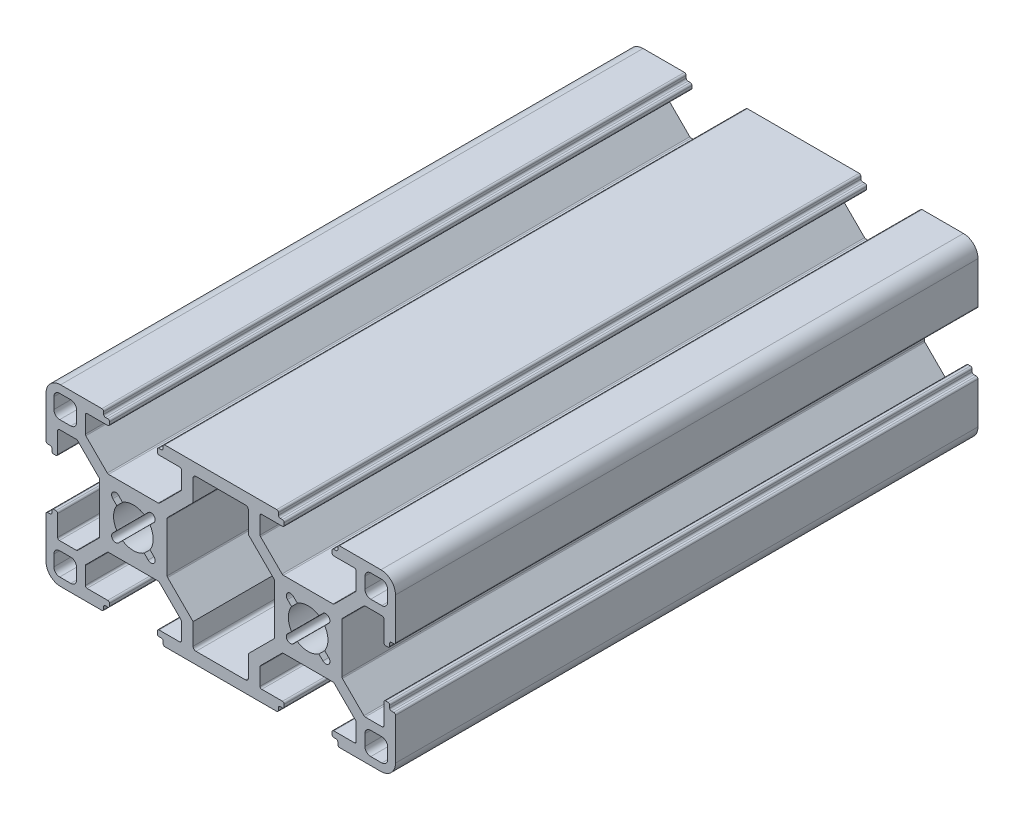
SolidWorks part; units mm, degrees
ref_plane "前视基准面" through (0, 0, 0) normal (0, 0, 1) x (1, 0, 0)
ref_plane "上视基准面" through (0, 0, 0) normal (0, 1, 0) x (1, 0, 0)
ref_plane "右视基准面" through (0, 0, 0) normal (1, 0, 0) x (0, 0, -1)
sketch "草图1" plane through (0, 0, 0) normal (0, 0, 1) x (1, 0, 0)
  line B0 (39.75, -10.75) -> (39.75, -12.65)
  line B1 (40.75, -13.65) -> (42.65, -13.65)
  line B2 (43.65, -12.65) -> (43.65, -10.75)
  line B3 (42.65, -9.75) -> (40.75, -9.75)
  line B4 (7.95, -13) -> (4.4, -13)
  line B5 (4.1, -13.3) -> (4.1, -13.7)
  line B6 (4.4, -14) -> (4.8, -14)
  line B7 (5.1, -14.3) -> (5.1, -14.7)
  line B8 (5.4, -15) -> (24.6, -15)
  line B9 (24.9, -14.7) -> (24.9, -14.3)
  line B10 (25.2, -14) -> (25.6, -14)
  line B11 (25.9, -13.7) -> (25.9, -13.3)
  line B12 (25.6, -13) -> (22.05, -13)
  line B13 (21.75, -12.7) -> (21.75, -9.7885)
  line B14 (21.8379, -9.5763) -> (25.5263, -5.8879)
  line B15 (25.7385, -5.8) -> (34.2615, -5.8)
  line B16 (34.4737, -5.8879) -> (38.1621, -9.5763)
  line B17 (38.25, -9.7885) -> (38.25, -12.7)
  line B18 (37.95, -13) -> (34.4, -13)
  line B19 (34.1, -13.3) -> (34.1, -13.7)
  line B20 (34.4, -14) -> (34.8, -14)
  line B21 (35.1, -14.3) -> (35.1, -14.7)
  line B22 (35.4, -15) -> (42.5, -15)
  line B23 (45, -12.5) -> (45, -5.4)
  line B24 (44.7, -5.1) -> (44.3, -5.1)
  line B25 (44, -4.8) -> (44, -4.4)
  line B26 (43.7, -4.1) -> (43.3, -4.1)
  line B27 (43, -4.4) -> (43, -7.95)
  line B28 (42.7, -8.25) -> (39.7885, -8.25)
  line B29 (39.5763, -8.1621) -> (35.8879, -4.4737)
  line B30 (35.8, -4.2615) -> (35.8, 4.2615)
  line B31 (35.8879, 4.4737) -> (39.5763, 8.1621)
  line B32 (39.7885, 8.25) -> (42.7, 8.25)
  line B33 (43, 7.95) -> (43, 4.4)
  line B34 (43.3, 4.1) -> (43.7, 4.1)
  line B35 (44, 4.4) -> (44, 4.8)
  line B36 (44.3, 5.1) -> (44.7, 5.1)
  line B37 (45, 5.4) -> (45, 12.5)
  line B38 (42.5, 15) -> (35.4, 15)
  line B39 (35.1, 14.7) -> (35.1, 14.3)
  line B40 (34.8, 14) -> (34.4, 14)
  line B41 (34.1, 13.7) -> (34.1, 13.3)
  line B42 (34.4, 13) -> (37.95, 13)
  line B43 (38.25, 12.7) -> (38.25, 9.7885)
  line B44 (38.1621, 9.5763) -> (34.4737, 5.8879)
  line B45 (34.2615, 5.8) -> (25.7385, 5.8)
  line B46 (25.5263, 5.8879) -> (21.8379, 9.5763)
  line B47 (21.75, 9.7885) -> (21.75, 12.7)
  line B48 (22.05, 13) -> (25.6, 13)
  line B49 (25.9, 13.3) -> (25.9, 13.7)
  line B50 (25.6, 14) -> (25.2, 14)
  line B51 (24.9, 14.3) -> (24.9, 14.7)
  line B52 (24.6, 15) -> (5.4, 15)
  line B53 (5.1, 14.7) -> (5.1, 14.3)
  line B54 (4.8, 14) -> (4.4, 14)
  line B55 (4.1, 13.7) -> (4.1, 13.3)
  line B56 (4.4, 13) -> (7.95, 13)
  line B57 (8.25, 12.7) -> (8.25, 9.7885)
  line B58 (8.1621, 9.5763) -> (4.4737, 5.8879)
  line B59 (4.2615, 5.8) -> (-4.2615, 5.8)
  line B60 (-4.4737, 5.8879) -> (-8.1621, 9.5763)
  line B61 (-8.25, 9.7885) -> (-8.25, 12.7)
  line B62 (-7.95, 13) -> (-4.4, 13)
  line B63 (-4.1, 13.3) -> (-4.1, 13.7)
  line B64 (-4.4, 14) -> (-4.8, 14)
  line B65 (-5.1, 14.3) -> (-5.1, 14.7)
  line B66 (-5.4, 15) -> (-12.5, 15)
  line B67 (-15, 12.5) -> (-15, 5.4)
  line B68 (-14.7, 5.1) -> (-14.3, 5.1)
  line B69 (-14, 4.8) -> (-14, 4.4)
  line B70 (-13.7, 4.1) -> (-13.3, 4.1)
  line B71 (-13, 4.4) -> (-13, 7.95)
  line B72 (-12.7, 8.25) -> (-9.7885, 8.25)
  line B73 (-9.5763, 8.1621) -> (-5.8879, 4.4737)
  line B74 (-5.8, 4.2615) -> (-5.8, -4.2615)
  line B75 (-5.8879, -4.4737) -> (-9.5763, -8.1621)
  line B76 (-9.7885, -8.25) -> (-12.7, -8.25)
  line B77 (-13, -7.95) -> (-13, -4.4)
  line B78 (-13.3, -4.1) -> (-13.7, -4.1)
  line B79 (-14, -4.4) -> (-14, -4.8)
  line B80 (-14.3, -5.1) -> (-14.7, -5.1)
  line B81 (-15, -5.4) -> (-15, -12.5)
  line B82 (-12.5, -15) -> (-5.4, -15)
  line B83 (-5.1, -14.7) -> (-5.1, -14.3)
  line B84 (-4.8, -14) -> (-4.4, -14)
  line B85 (-4.1, -13.7) -> (-4.1, -13.3)
  line B86 (-4.4, -13) -> (-7.95, -13)
  line B87 (-8.25, -12.7) -> (-8.25, -9.7885)
  line B88 (-8.1621, -9.5763) -> (-4.4737, -5.8879)
  line B89 (-4.2615, -5.8) -> (4.2615, -5.8)
  line B90 (4.4737, -5.8879) -> (8.1621, -9.5763)
  line B91 (8.25, -9.7885) -> (8.25, -12.7)
  line B92 (40.75, 9.75) -> (42.65, 9.75)
  line B93 (43.65, 10.75) -> (43.65, 12.65)
  line B94 (42.65, 13.65) -> (40.75, 13.65)
  line B95 (39.75, 12.65) -> (39.75, 10.75)
  line B96 (32.5456, 3.5355) -> (31.8577, 2.8476)
  line B97 (28.1423, 2.8476) -> (27.4544, 3.5355)
  line B98 (26.4645, 2.5456) -> (27.1524, 1.8577)
  line B99 (27.1524, -1.8577) -> (26.4645, -2.5456)
  line B100 (27.4544, -3.5355) -> (28.1423, -2.8476)
  line B101 (31.8577, -2.8476) -> (32.5456, -3.5355)
  line B102 (33.5355, -2.5456) -> (32.8476, -1.8577)
  line B103 (32.8476, 1.8577) -> (33.5355, 2.5456)
  line B104 (10.75, -13) -> (19.25, -13)
  line B105 (19.75, -12.5) -> (19.75, -8.8358)
  line B106 (19.75, -8.8358) -> (24.1121, -4.4737)
  line B107 (24.2, -4.2615) -> (24.2, 4.2615)
  line B108 (24.1121, 4.4737) -> (19.75, 8.8358)
  line B109 (19.75, 8.8358) -> (19.75, 12.5)
  line B110 (19.25, 13) -> (10.75, 13)
  line B111 (10.25, 12.5) -> (10.25, 8.8358)
  line B112 (10.25, 8.8358) -> (5.8879, 4.4737)
  line B113 (5.8, 4.2615) -> (5.8, -4.2615)
  line B114 (5.8879, -4.4737) -> (10.25, -8.8358)
  line B115 (10.25, -8.8358) -> (10.25, -12.5)
  line B116 (2.5456, 3.5355) -> (1.8577, 2.8476)
  line B117 (-1.8577, 2.8476) -> (-2.5456, 3.5355)
  line B118 (-3.5355, 2.5456) -> (-2.8476, 1.8577)
  line B119 (-2.8476, -1.8577) -> (-3.5355, -2.5456)
  line B120 (-2.5456, -3.5355) -> (-1.8577, -2.8476)
  line B121 (1.8577, -2.8476) -> (2.5456, -3.5355)
  line B122 (3.5355, -2.5456) -> (2.8476, -1.8577)
  line B123 (2.8476, 1.8577) -> (3.5355, 2.5456)
  line B124 (-9.75, 10.75) -> (-9.75, 12.65)
  line B125 (-10.75, 13.65) -> (-12.65, 13.65)
  line B126 (-13.65, 12.65) -> (-13.65, 10.75)
  line B127 (-12.65, 9.75) -> (-10.75, 9.75)
  line B128 (-10.75, -9.75) -> (-12.65, -9.75)
  line B129 (-13.65, -10.75) -> (-13.65, -12.65)
  line B130 (-12.65, -13.65) -> (-10.75, -13.65)
  line B131 (-9.75, -12.65) -> (-9.75, -10.75)
  arc B132 (40.75, -9.75) -> (39.75, -10.75) centre (40.75, -10.75) ccw
  arc B133 (39.75, -12.65) -> (40.75, -13.65) centre (40.75, -12.65) ccw
  arc B134 (42.65, -13.65) -> (43.65, -12.65) centre (42.65, -12.65) ccw
  arc B135 (43.65, -10.75) -> (42.65, -9.75) centre (42.65, -10.75) ccw
  arc B136 (4.4, -13) -> (4.1, -13.3) centre (4.4, -13.3) ccw
  arc B137 (4.1, -13.7) -> (4.4, -14) centre (4.4, -13.7) ccw
  arc B138 (5.1, -14.3) -> (4.8, -14) centre (4.8, -14.3) ccw
  arc B139 (5.1, -14.7) -> (5.4, -15) centre (5.4, -14.7) ccw
  arc B140 (24.6, -15) -> (24.9, -14.7) centre (24.6, -14.7) ccw
  arc B141 (25.2, -14) -> (24.9, -14.3) centre (25.2, -14.3) ccw
  arc B142 (25.6, -14) -> (25.9, -13.7) centre (25.6, -13.7) ccw
  arc B143 (25.9, -13.3) -> (25.6, -13) centre (25.6, -13.3) ccw
  arc B144 (21.75, -12.7) -> (22.05, -13) centre (22.05, -12.7) ccw
  arc B145 (21.8379, -9.5763) -> (21.75, -9.7885) centre (22.05, -9.7885) ccw
  arc B146 (25.7385, -5.8) -> (25.5263, -5.8879) centre (25.7385, -6.1) ccw
  arc B147 (34.4737, -5.8879) -> (34.2615, -5.8) centre (34.2615, -6.1) ccw
  arc B148 (38.25, -9.7885) -> (38.1621, -9.5763) centre (37.95, -9.7885) ccw
  arc B149 (37.95, -13) -> (38.25, -12.7) centre (37.95, -12.7) ccw
  arc B150 (34.4, -13) -> (34.1, -13.3) centre (34.4, -13.3) ccw
  arc B151 (34.1, -13.7) -> (34.4, -14) centre (34.4, -13.7) ccw
  arc B152 (35.1, -14.3) -> (34.8, -14) centre (34.8, -14.3) ccw
  arc B153 (35.1, -14.7) -> (35.4, -15) centre (35.4, -14.7) ccw
  arc B154 (42.5, -15) -> (45, -12.5) centre (42.5, -12.5) ccw
  arc B155 (45, -5.4) -> (44.7, -5.1) centre (44.7, -5.4) ccw
  arc B156 (44, -4.8) -> (44.3, -5.1) centre (44.3, -4.8) ccw
  arc B157 (44, -4.4) -> (43.7, -4.1) centre (43.7, -4.4) ccw
  arc B158 (43.3, -4.1) -> (43, -4.4) centre (43.3, -4.4) ccw
  arc B159 (42.7, -8.25) -> (43, -7.95) centre (42.7, -7.95) ccw
  arc B160 (39.5763, -8.1621) -> (39.7885, -8.25) centre (39.7885, -7.95) ccw
  arc B161 (35.8, -4.2615) -> (35.8879, -4.4737) centre (36.1, -4.2615) ccw
  arc B162 (35.8879, 4.4737) -> (35.8, 4.2615) centre (36.1, 4.2615) ccw
  arc B163 (39.7885, 8.25) -> (39.5763, 8.1621) centre (39.7885, 7.95) ccw
  arc B164 (43, 7.95) -> (42.7, 8.25) centre (42.7, 7.95) ccw
  arc B165 (43, 4.4) -> (43.3, 4.1) centre (43.3, 4.4) ccw
  arc B166 (43.7, 4.1) -> (44, 4.4) centre (43.7, 4.4) ccw
  arc B167 (44.3, 5.1) -> (44, 4.8) centre (44.3, 4.8) ccw
  arc B168 (44.7, 5.1) -> (45, 5.4) centre (44.7, 5.4) ccw
  arc B169 (45, 12.5) -> (42.5, 15) centre (42.5, 12.5) ccw
  arc B170 (35.4, 15) -> (35.1, 14.7) centre (35.4, 14.7) ccw
  arc B171 (34.8, 14) -> (35.1, 14.3) centre (34.8, 14.3) ccw
  arc B172 (34.4, 14) -> (34.1, 13.7) centre (34.4, 13.7) ccw
  arc B173 (34.1, 13.3) -> (34.4, 13) centre (34.4, 13.3) ccw
  arc B174 (38.25, 12.7) -> (37.95, 13) centre (37.95, 12.7) ccw
  arc B175 (38.1621, 9.5763) -> (38.25, 9.7885) centre (37.95, 9.7885) ccw
  arc B176 (34.2615, 5.8) -> (34.4737, 5.8879) centre (34.2615, 6.1) ccw
  arc B177 (25.5263, 5.8879) -> (25.7385, 5.8) centre (25.7385, 6.1) ccw
  arc B178 (21.75, 9.7885) -> (21.8379, 9.5763) centre (22.05, 9.7885) ccw
  arc B179 (22.05, 13) -> (21.75, 12.7) centre (22.05, 12.7) ccw
  arc B180 (25.6, 13) -> (25.9, 13.3) centre (25.6, 13.3) ccw
  arc B181 (25.9, 13.7) -> (25.6, 14) centre (25.6, 13.7) ccw
  arc B182 (24.9, 14.3) -> (25.2, 14) centre (25.2, 14.3) ccw
  arc B183 (24.9, 14.7) -> (24.6, 15) centre (24.6, 14.7) ccw
  arc B184 (5.4, 15) -> (5.1, 14.7) centre (5.4, 14.7) ccw
  arc B185 (4.8, 14) -> (5.1, 14.3) centre (4.8, 14.3) ccw
  arc B186 (4.4, 14) -> (4.1, 13.7) centre (4.4, 13.7) ccw
  arc B187 (4.1, 13.3) -> (4.4, 13) centre (4.4, 13.3) ccw
  arc B188 (8.25, 12.7) -> (7.95, 13) centre (7.95, 12.7) ccw
  arc B189 (8.1621, 9.5763) -> (8.25, 9.7885) centre (7.95, 9.7885) ccw
  arc B190 (4.2615, 5.8) -> (4.4737, 5.8879) centre (4.2615, 6.1) ccw
  arc B191 (-4.4737, 5.8879) -> (-4.2615, 5.8) centre (-4.2615, 6.1) ccw
  arc B192 (-8.25, 9.7885) -> (-8.1621, 9.5763) centre (-7.95, 9.7885) ccw
  arc B193 (-7.95, 13) -> (-8.25, 12.7) centre (-7.95, 12.7) ccw
  arc B194 (-4.4, 13) -> (-4.1, 13.3) centre (-4.4, 13.3) ccw
  arc B195 (-4.1, 13.7) -> (-4.4, 14) centre (-4.4, 13.7) ccw
  arc B196 (-5.1, 14.3) -> (-4.8, 14) centre (-4.8, 14.3) ccw
  arc B197 (-5.1, 14.7) -> (-5.4, 15) centre (-5.4, 14.7) ccw
  arc B198 (-12.5, 15) -> (-15, 12.5) centre (-12.5, 12.5) ccw
  arc B199 (-15, 5.4) -> (-14.7, 5.1) centre (-14.7, 5.4) ccw
  arc B200 (-14, 4.8) -> (-14.3, 5.1) centre (-14.3, 4.8) ccw
  arc B201 (-14, 4.4) -> (-13.7, 4.1) centre (-13.7, 4.4) ccw
  arc B202 (-13.3, 4.1) -> (-13, 4.4) centre (-13.3, 4.4) ccw
  arc B203 (-12.7, 8.25) -> (-13, 7.95) centre (-12.7, 7.95) ccw
  arc B204 (-9.5763, 8.1621) -> (-9.7885, 8.25) centre (-9.7885, 7.95) ccw
  arc B205 (-5.8, 4.2615) -> (-5.8879, 4.4737) centre (-6.1, 4.2615) ccw
  arc B206 (-5.8879, -4.4737) -> (-5.8, -4.2615) centre (-6.1, -4.2615) ccw
  arc B207 (-9.7885, -8.25) -> (-9.5763, -8.1621) centre (-9.7885, -7.95) ccw
  arc B208 (-13, -7.95) -> (-12.7, -8.25) centre (-12.7, -7.95) ccw
  arc B209 (-13, -4.4) -> (-13.3, -4.1) centre (-13.3, -4.4) ccw
  arc B210 (-13.7, -4.1) -> (-14, -4.4) centre (-13.7, -4.4) ccw
  arc B211 (-14.3, -5.1) -> (-14, -4.8) centre (-14.3, -4.8) ccw
  arc B212 (-14.7, -5.1) -> (-15, -5.4) centre (-14.7, -5.4) ccw
  arc B213 (-15, -12.5) -> (-12.5, -15) centre (-12.5, -12.5) ccw
  arc B214 (-5.4, -15) -> (-5.1, -14.7) centre (-5.4, -14.7) ccw
  arc B215 (-4.8, -14) -> (-5.1, -14.3) centre (-4.8, -14.3) ccw
  arc B216 (-4.4, -14) -> (-4.1, -13.7) centre (-4.4, -13.7) ccw
  arc B217 (-4.1, -13.3) -> (-4.4, -13) centre (-4.4, -13.3) ccw
  arc B218 (-8.25, -12.7) -> (-7.95, -13) centre (-7.95, -12.7) ccw
  arc B219 (-8.1621, -9.5763) -> (-8.25, -9.7885) centre (-7.95, -9.7885) ccw
  arc B220 (-4.2615, -5.8) -> (-4.4737, -5.8879) centre (-4.2615, -6.1) ccw
  arc B221 (4.4737, -5.8879) -> (4.2615, -5.8) centre (4.2615, -6.1) ccw
  arc B222 (8.25, -9.7885) -> (8.1621, -9.5763) centre (7.95, -9.7885) ccw
  arc B223 (7.95, -13) -> (8.25, -12.7) centre (7.95, -12.7) ccw
  arc B224 (42.65, 9.75) -> (43.65, 10.75) centre (42.65, 10.75) ccw
  arc B225 (43.65, 12.65) -> (42.65, 13.65) centre (42.65, 12.65) ccw
  arc B226 (40.75, 13.65) -> (39.75, 12.65) centre (40.75, 12.65) ccw
  arc B227 (39.75, 10.75) -> (40.75, 9.75) centre (40.75, 10.75) ccw
  arc B228 (31.8577, 2.8476) -> (28.1423, 2.8476) centre (30, 0) ccw
  arc B229 (27.4544, 3.5355) -> (26.4645, 2.5456) centre (26.9594, 3.0406) ccw
  arc B230 (27.1524, 1.8577) -> (27.1524, -1.8577) centre (30, 0) ccw
  arc B231 (26.4645, -2.5456) -> (27.4544, -3.5355) centre (26.9594, -3.0406) ccw
  arc B232 (28.1423, -2.8476) -> (31.8577, -2.8476) centre (30, 0) ccw
  arc B233 (32.5456, -3.5355) -> (33.5355, -2.5456) centre (33.0406, -3.0406) ccw
  arc B234 (32.8476, -1.8577) -> (32.8476, 1.8577) centre (30, 0) ccw
  arc B235 (33.5355, 2.5456) -> (32.5456, 3.5355) centre (33.0406, 3.0406) ccw
  arc B236 (10.25, -12.5) -> (10.75, -13) centre (10.75, -12.5) ccw
  arc B237 (19.25, -13) -> (19.75, -12.5) centre (19.25, -12.5) ccw
  arc B238 (24.1121, -4.4737) -> (24.2, -4.2615) centre (23.9, -4.2615) ccw
  arc B239 (24.2, 4.2615) -> (24.1121, 4.4737) centre (23.9, 4.2615) ccw
  arc B240 (19.75, 12.5) -> (19.25, 13) centre (19.25, 12.5) ccw
  arc B241 (10.75, 13) -> (10.25, 12.5) centre (10.75, 12.5) ccw
  arc B242 (5.8879, 4.4737) -> (5.8, 4.2615) centre (6.1, 4.2615) ccw
  arc B243 (5.8, -4.2615) -> (5.8879, -4.4737) centre (6.1, -4.2615) ccw
  arc B244 (1.8577, 2.8476) -> (-1.8577, 2.8476) centre (0, 0) ccw
  arc B245 (-2.5456, 3.5355) -> (-3.5355, 2.5456) centre (-3.0406, 3.0406) ccw
  arc B246 (-2.8476, 1.8577) -> (-2.8476, -1.8577) centre (0, 0) ccw
  arc B247 (-3.5355, -2.5456) -> (-2.5456, -3.5355) centre (-3.0406, -3.0406) ccw
  arc B248 (-1.8577, -2.8476) -> (1.8577, -2.8476) centre (0, 0) ccw
  arc B249 (2.5456, -3.5355) -> (3.5355, -2.5456) centre (3.0406, -3.0406) ccw
  arc B250 (2.8476, -1.8577) -> (2.8476, 1.8577) centre (0, 0) ccw
  arc B251 (3.5355, 2.5456) -> (2.5456, 3.5355) centre (3.0406, 3.0406) ccw
  arc B252 (-9.75, 12.65) -> (-10.75, 13.65) centre (-10.75, 12.65) ccw
  arc B253 (-12.65, 13.65) -> (-13.65, 12.65) centre (-12.65, 12.65) ccw
  arc B254 (-13.65, 10.75) -> (-12.65, 9.75) centre (-12.65, 10.75) ccw
  arc B255 (-10.75, 9.75) -> (-9.75, 10.75) centre (-10.75, 10.75) ccw
  arc B256 (-9.75, -10.75) -> (-10.75, -9.75) centre (-10.75, -10.75) ccw
  arc B257 (-12.65, -9.75) -> (-13.65, -10.75) centre (-12.65, -10.75) ccw
  arc B258 (-13.65, -12.65) -> (-12.65, -13.65) centre (-12.65, -12.65) ccw
  arc B259 (-10.75, -13.65) -> (-9.75, -12.65) centre (-10.75, -12.65) ccw
sketch_block_instance "A$C1A6A0ABC-1"
sketch_block "A$C1A6A0ABC"
extrude "凸台-拉伸1" add sketch "草图1" along normal blind 100
